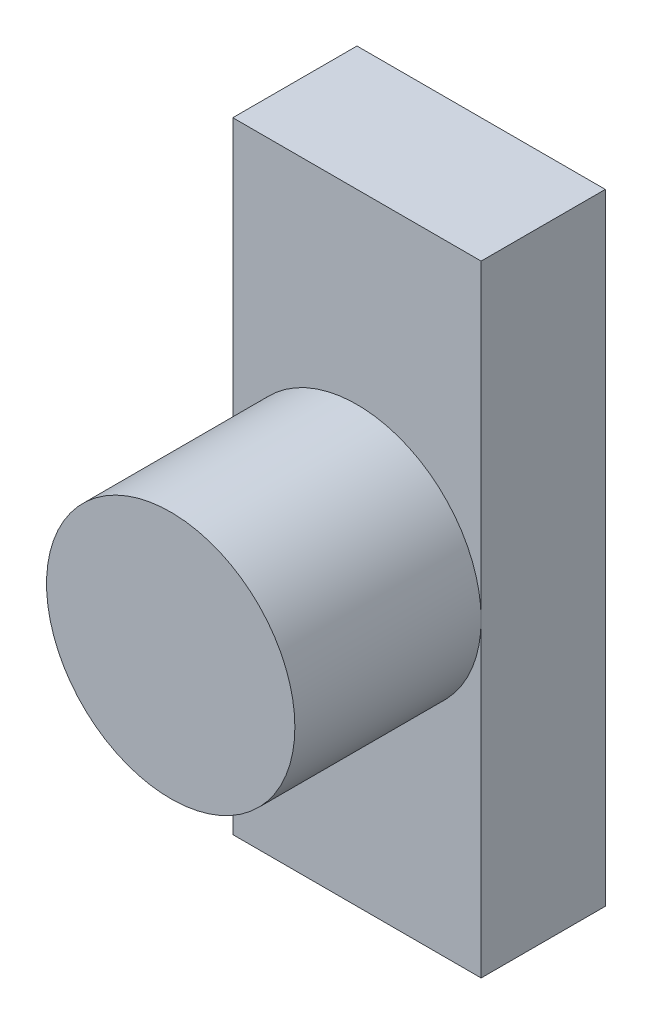
SolidWorks part; units mm, degrees
ref_plane "Front Plane" through (0, 0, 0) normal (0, 0, 1) x (1, 0, 0)
ref_plane "Top Plane" through (0, 0, 0) normal (0, 1, 0) x (1, 0, 0)
ref_plane "Right Plane" through (0, 0, 0) normal (1, 0, 0) x (0, 0, -1)
sketch "Sketch1" plane through (0, 0, 0) normal (0, 0, 1) x (1, 0, 0)
  line L1 (0, 0) -> (-4, 0)
  line L2 (0, 0) -> (0, 10)
  line L3 (0, 10) -> (-4, 10)
  line L4 (-4, 0) -> (-4, 10)
  dimension "D1" = 10
  dimension "D2" = 4
extrude "Boss-Extrude1" add sketch "Sketch1" along normal blind 2
sketch "Sketch2" plane through (0, 0, 2) normal (0, 0, 1) x (1, 0, 0)
  line L0 (-4, 5) -> (0.1795, 5) construction
  line L1 (-4, 10) -> (-4, 0) construction
  line L2 (-2, 10) -> (-2, -0.3231) construction
  line L3 (0, 10) -> (-4, 10) construction
  circle A0 centre (-2, 5) radius 2
  dimension "D1" = 4
extrude "Boss-Extrude2" add sketch "Sketch2" along normal blind 3
